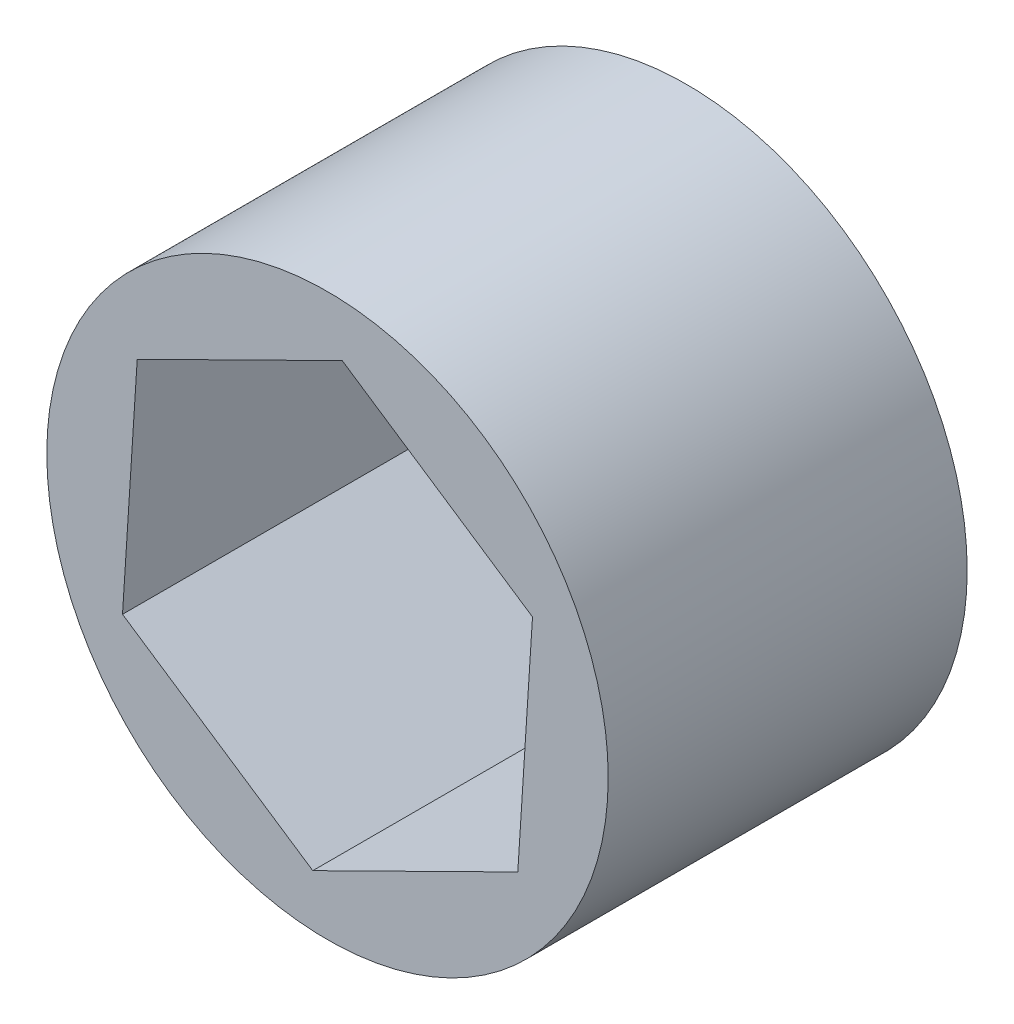
SolidWorks part; units mm, degrees
ref_plane "Front Plane" through (0, 0, 0) normal (0, 0, 1) x (1, 0, 0)
ref_plane "Top Plane" through (0, 0, 0) normal (0, 1, 0) x (1, 0, 0)
ref_plane "Right Plane" through (0, 0, 0) normal (1, 0, 0) x (0, 0, -1)
sketch "Sketch1" plane through (0, 0, 0) normal (0, 0, 1) x (1, 0, 0)
  line L1 (-6.1009, 4.0673) -> (-6.5728, -3.2499)
  line L2 (-6.5728, -3.2499) -> (-0.4719, -7.3171)
  line L3 (-0.4719, -7.3171) -> (6.1009, -4.0673)
  line L4 (6.1009, -4.0673) -> (6.5728, 3.2499)
  line L5 (6.5728, 3.2499) -> (0.4719, 7.3171)
  line L6 (0.4719, 7.3171) -> (-6.1009, 4.0673)
  circle A0 centre (0, 0) radius 6.35 construction
  circle A1 centre (0, 0) radius 9
  dimension "D1" = 12.7
  dimension "D2" = 18
extrude "Boss-Extrude1" add sketch "Sketch1" along normal blind 11.51
